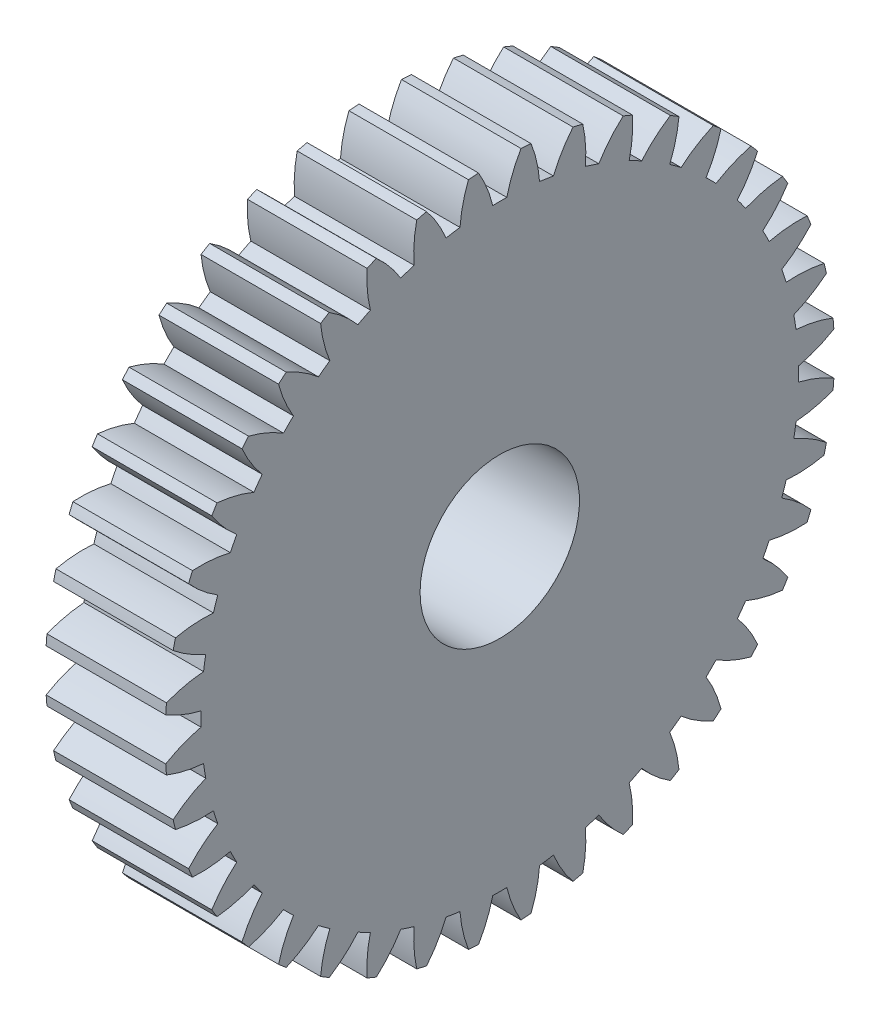
SolidWorks part; units mm, degrees
material "AISI 1045 Steel, cold drawn"
ref_plane "Plane1" through (0, 0, 0) normal (0, 0, 1) x (1, 0, 0)
ref_plane "Plane2" through (0, 0, 0) normal (0, 1, 0) x (1, 0, 0)
ref_plane "Plane3" through (0, 0, 0) normal (1, 0, 0) x (0, 0, -1)
sketch "HoldingSke" plane through (0, 0, 0) normal (0, 1, 0) x (1, 0, 0)
  line L0 (0, 0) -> (0.383, -0.3214)
  line L1 (-15, 0) -> (100, 0) construction
  line L2 (0, 0) -> (-2.1039, 2.3779)
  line L3 (0, 0) -> (-11.863, 4.5341)
  line L4 (0, 0) -> (6.6156, 5.5511)
  line L5 (0, 0) -> (-46.8476, -17.4728)
  line L6 (0, 0) -> (-12.4344, -8.3896)
  line L7 (-2.1039, 2.3779) -> (8.6586, 51.2059)
  line L8 (-76.2, 54.61) -> (-73.4, 54.61)
  line L9 (-71.009, 38.7566) -> (-53.1078, 45.2721)
  line L10 (-76.2, 71.12) -> (104.1128, 71.12)
  line L11 (0, 0) -> (-15, 0)
  line L12 (-76.2, 101.6) -> (-76.133, 101.6)
  line L13 (24.9733, 27.94) -> (52.9518, 28.4284)
  line L14 (24.9733, 27.94) -> (24.9743, 27.94)
  line L15 (24.9733, 27.94) -> (100.4006, 29.5858)
  line L16 (-63.627, -2) -> (-12.827, -2)
  circle A0 centre (0, 0) radius 10
  circle A1 centre (0, 0) radius 37.499
  circle A2 centre (0, 0) radius 37.5
  circle A3 centre (0, 0) radius 10
  dimension "MHD" = 74.998
  dimension "Hub_dia" = 75
  dimension "Bore" = 20
  dimension "MBD" = 20
  dimension "Num_teeth" = 40
  dimension "Pitch" = 0.5
  dimension "Overall_len" = 50
  dimension "Show_teeth" = 40
  dimension "Thickness" = 15
  dimension "OAL" = 50.0001
  dimension "T_dim" = 2.8
  dimension "Ap" = 20
  dimension "H" = 19.05
  dimension "Pitch_radius" = 180.3128
  dimension "Width" = 15
  dimension "Backlash" = 0.067
  dimension "Addendum_fac" = 1
  dimension "Dedendum_fac" = 1.25
  dimension "Clearance_fac" = 0.25
  dimension "Dedendum_add" = 0.001
  dimension "Module" = 2
sketch "BasProSke" plane through (0, 0, 0) normal (0, 1, 0) x (1, 0, 0)
  line L0 (-10, 0) -> (60, 0) construction
  line L1 (0, 0) -> (0, 42)
  line L2 (0, 0) -> (15, 0)
  line L3 (15, 0) -> (15, 42)
  line L4 (15, 42) -> (0, 42)
  dimension "Thickness" = 15
  dimension "Diameter" = 84
revolve "Base-Revolve" add sketch "BasProSke" angle 360 about L0
sketch "TooCutSke" plane through (0, 0, 0) normal (1, 0, 0) x (0, 0, -1)
  line L1 (0, 0) -> (0, 107) construction
  line L2 (0, 0) -> (-1.6876, 39.9644) construction
  line L3 (0, 0) -> (-6.2726, 79.7007) construction
  line L4 (-1.6876, 39.9644) -> (-3.1363, 39.8504) construction
  arc A0 (0.8828, 37.4886) -> (-0.8828, 37.4886) centre (0, 0) ccw
  arc A1 (2.6784, 41.94) -> (-2.6784, 41.94) centre (0, 0) ccw
  circle A2 centre (0, 0) radius 40 construction
  circle A3 centre (0, 0) radius 37.5877 construction
  arc A4 (-0.8828, 37.4886) -> (-2.6784, 41.94) centre (-16.451, 33.7965) ccw
  arc A5 (2.6784, 41.94) -> (0.8828, 37.4886) centre (16.451, 33.7965) ccw
  dimension "Root_dia" = 74.998
  dimension "Overcut_dia" = 84.0508
  dimension "Pitch_dia" = 80
  dimension "Base_dia" = 75.1754
  dimension "Flank_rad" = 16
  dimension "Half_ang" = 4.5
  dimension "Half_CT" = 1.4531
extrude "ToothCut" cut sketch "TooCutSke" along normal through all
fillet "Breaks" [suppressed] radius 0.04
fillet "RootFillets" [suppressed] radius 0.501
pattern_circular "TeethCuts" count 40 every 9 about axis through (-10, 0, 0) along (1, 0, 0) of "ToothCut", "RootFillets", "Breaks"
sketch "HubNeaOneSke" plane through (0, 0, 0) normal (-1, 0, 0) x (0, 0, 1)
  circle A0 centre (0, 0) radius 37.499
  dimension "Diameter" = 74.998
extrude "HubNearOne" [suppressed] add sketch "HubNeaOneSke" along normal blind 35.0001
sketch "HubNeaBotSke" plane through (0, 0, 0) normal (-1, 0, 0) x (0, 0, 1)
  circle A0 centre (0, 0) radius 37.499
  dimension "Diameter" = 74.998
extrude "HubNearBoth" [suppressed] add sketch "HubNeaBotSke" along normal blind 17.5001
ref_plane "FarPln" through (15, 0, 0) normal (1, 0, 0) x (0, 0, -1)
sketch "HubFarSke" plane through (15, 0, 0) normal (1, 0, 0) x (0, 0, -1)
  circle A0 centre (0, 0) radius 37.499
  dimension "Diameter" = 74.998
extrude "HubFar" [suppressed] add sketch "HubFarSke" along normal blind 17.5001
sketch "BorSke" plane through (0, 0, 0) normal (1, 0, 0) x (0, 0, -1)
  circle A0 centre (0, 0) radius 10
  dimension "Diameter" = 20
extrude "Bore" cut sketch "BorSke" along normal mid plane 100.0002
sketch "KeySke" plane through (0, 0, 0) normal (1, 0, 0) x (0, 0, -1)
  line L0 (-3, 0) -> (-3, 12.8)
  line L1 (-3, 12.8) -> (3, 12.8)
  line L2 (3, 12.8) -> (3, 0)
  line L3 (0, 0) -> (0, 34) construction
  line L4 (-3, 0) -> (3, 0)
  dimension "Offset" = 12.8
  dimension "Width" = 6
extrude "Keyway" [suppressed] cut sketch "KeySke" along normal mid plane 100.0002
pattern_circular "Keyway2" [suppressed] count 2 every 90 about axis through (-10, 0, 0) along (1, 0, 0)
equation "' \"Module@HoldingSke\" = 6.35"
equation "' \"Num_teeth@HoldingSke\" = 12"
equation "' \"Ap@HoldingSke\" =  20"
equation "' \"Ap@HoldingSke\" = 20"
equation "' \"Width@HoldingSke\" = 0.5 * 25.4"
equation "' \"Hub_dia@HoldingSke\"= 1 * 25.4"
equation "' \"Hub_dia@HoldingSke\" = 1 * 25.4"
equation "' \"Overall_len@HoldingSke\" = 1.0 * 25.4"
equation "' \"Bore@HoldingSke\" = 0.75 * 25.4"
equation "' \"T_dim@HoldingSke\" = 0.1 * 25.4"
equation "' \"Width@KeySke\" = 0.25 * 25.4"
equation "' \"Show_teeth@HoldingSke\" = 13"
equation "' \"Backlash@HoldingSke\" = 0.009 * 25.4"
equation "' \"Addendum_fac@HoldingSke\" = 1.0"
equation "' \"Dedendum_fac@HoldingSke\" = 1.25"
equation "' \"Dedendum_add@HoldingSke\" = 0.00005 * 25.4"
equation "' \"Clearance_fac@HoldingSke\" = 0.25"
equation "\"Pitch@HoldingSke\" = 1 / \"Module@HoldingSke\""
equation "\"Overcut_dia@TooCutSke\" = (\"Num_teeth@HoldingSke\" + 2 * \"Addendum_fac@HoldingSke\") / \"Pitch@HoldingSke\" + 0.002 * 25.4"
equation "\"Pitch_dia@TooCutSke\" = \"Num_teeth@HoldingSke\" / \"Pitch@HoldingSke\""
equation "\"Base_dia@TooCutSke\" = \"Num_teeth@HoldingSke\" / \"Pitch@HoldingSke\" * cos((\"Ap@HoldingSke\"  * 3.14159265 / 180))"
equation "\"Root_dia@TooCutSke\" = (\"Num_teeth@HoldingSke\" + 2) / \"Pitch@HoldingSke\" - 2 * (\"Addendum_fac@HoldingSke\" + \"Dedendum_fac@HoldingSke\") / \"Pitch@HoldingSke\" - \"Dedendum_add@HoldingSke\" * 2"
equation "\"Half_ang@TooCutSke\" = 180 / \"Num_teeth@HoldingSke\""
equation "\"Half_CT@TooCutSke\" = \"Num_teeth@HoldingSke\" / \"Pitch@HoldingSke\" * sin((3.14159265 / 2 / \"Num_teeth@HoldingSke\")) / 2 - 7 * \"Backlash@HoldingSke\" / 4"
equation "\"Flank_rad@TooCutSke\" = \"Num_teeth@HoldingSke\" / \"Pitch@HoldingSke\" / 5"
equation "\"Radius@RootFillets\" = \"Clearance_fac@HoldingSke\" / \"Pitch@HoldingSke\" + \"Dedendum_add@HoldingSke\""
equation "\"Break_rad@Breaks\" = 0.02 / \"Pitch@HoldingSke\""
equation "\"Thickness@HoldingSke\" = \"Width@HoldingSke\""
equation "\"OAL@HoldingSke\" = \"Thickness@HoldingSke\""
equation "\"MHD@HoldingSke\" = (\"Num_teeth@HoldingSke\" + 2) / \"Pitch@HoldingSke\" - 2 * (\"Addendum_fac@HoldingSke\" + \"Dedendum_fac@HoldingSke\")  / \"Pitch@HoldingSke\" - \"Dedendum_add@HoldingSke\" * 2"
equation "\"MBD@HoldingSke\" = (\"Num_teeth@HoldingSke\" + 2) / \"Pitch@HoldingSke\" - 2 * (\"Addendum_fac@HoldingSke\" + \"Dedendum_fac@HoldingSke\")  / \"Pitch@HoldingSke\" - \"Dedendum_add@HoldingSke\" * 2 - 0.002 * 25.4"
equation "\"MHD@HoldingSke\" = ((sgn( \"MHD@HoldingSke\" - \"Hub_dia@HoldingSke\" )-1)*( \"MHD@HoldingSke\" - \"Hub_dia@HoldingSke\" ))/-2+ \"Hub_dia@HoldingSke\""
equation "\"MBD@HoldingSke\" = ((sgn( \"MBD@HoldingSke\" - \"Bore@HoldingSke\" )-1)*( \"MBD@HoldingSke\" - \"Bore@HoldingSke\" ))/-2+ \"Bore@HoldingSke\""
equation "\"OAL@HoldingSke\" = ((sgn( \"OAL@HoldingSke\" - \"Overall_len@HoldingSke\" )+1)*( \"OAL@HoldingSke\" - \"Overall_len@HoldingSke\" ))/2 + \"Overall_len@HoldingSke\" + 0.000002 * 25.4"
equation "\"Num_teeth@TeethCuts\" = int( \"Show_teeth@HoldingSke\" ) + 1"
equation "\"Num_teeth@TeethCuts\" = ((sgn( \"Num_teeth@TeethCuts\" - \"Num_teeth@HoldingSke\" )-1)*( \"Num_teeth@TeethCuts\" - \"Num_teeth@HoldingSke\" ))/-2+ \"Num_teeth@HoldingSke\""
equation "\"Num_teeth@TeethCuts\" = ((sgn( \"Num_teeth@TeethCuts\" - 2.0)+1)*( \"Num_teeth@TeethCuts\" - 2.0))/2 +2.0"
equation "\"Angle@TeethCuts\" = 360.0 / \"Num_teeth@HoldingSke\""
equation "\"Diameter@BasProSke\" = (\"Num_teeth@HoldingSke\" + 2 * \"Addendum_fac@HoldingSke\") / \"Pitch@HoldingSke\""
equation "\"Thickness@BasProSke\"  = \"Thickness@HoldingSke\""
equation "' \"Fillet_rad@BasProSke\" =  \"Thickness@HoldingSke\" * 0.05"
equation "' \"Fillet_rad@BasProSke\" = \"Thickness@HoldingSke\" * 0.05"
equation "\"MHD@HoldingSke\" = ((sgn( \"MHD@HoldingSke\" - \"Root_dia@TooCutSke\" )-1)*( \"MHD@HoldingSke\" - \"Root_dia@TooCutSke\" ))/-2+ \"Root_dia@TooCutSke\""
equation "\"Diameter@HubNeaOneSke\" = \"MHD@HoldingSke\""
equation "\"Length@HubNearOne\" = \"OAL@HoldingSke\" - \"Thickness@BasProSke\""
equation "\"Diameter@HubNeaBotSke\" = \"MHD@HoldingSke\""
equation "\"Length@HubNearBoth\" = ( \"OAL@HoldingSke\" - \"Thickness@BasProSke\" ) / 2.0"
equation "\"Thickness@FarPln\" = \"Thickness@BasProSke\""
equation "\"Diameter@HubFarSke\" = \"MHD@HoldingSke\""
equation "\"Length@HubFar\" = ( \"OAL@HoldingSke\" - \"Thickness@BasProSke\" ) / 2.0"
equation "\"Diameter@BorSke\" = \"MBD@HoldingSke\""
equation "\"D1@Bore\" = \"OAL@HoldingSke\" * 2.0"
equation "\"D1@Keyway\" = \"OAL@HoldingSke\" * 2.0"
equation "\"Offset@KeySke\" = \"T_dim@HoldingSke\" + \"MBD@HoldingSke\" / 2.0"
